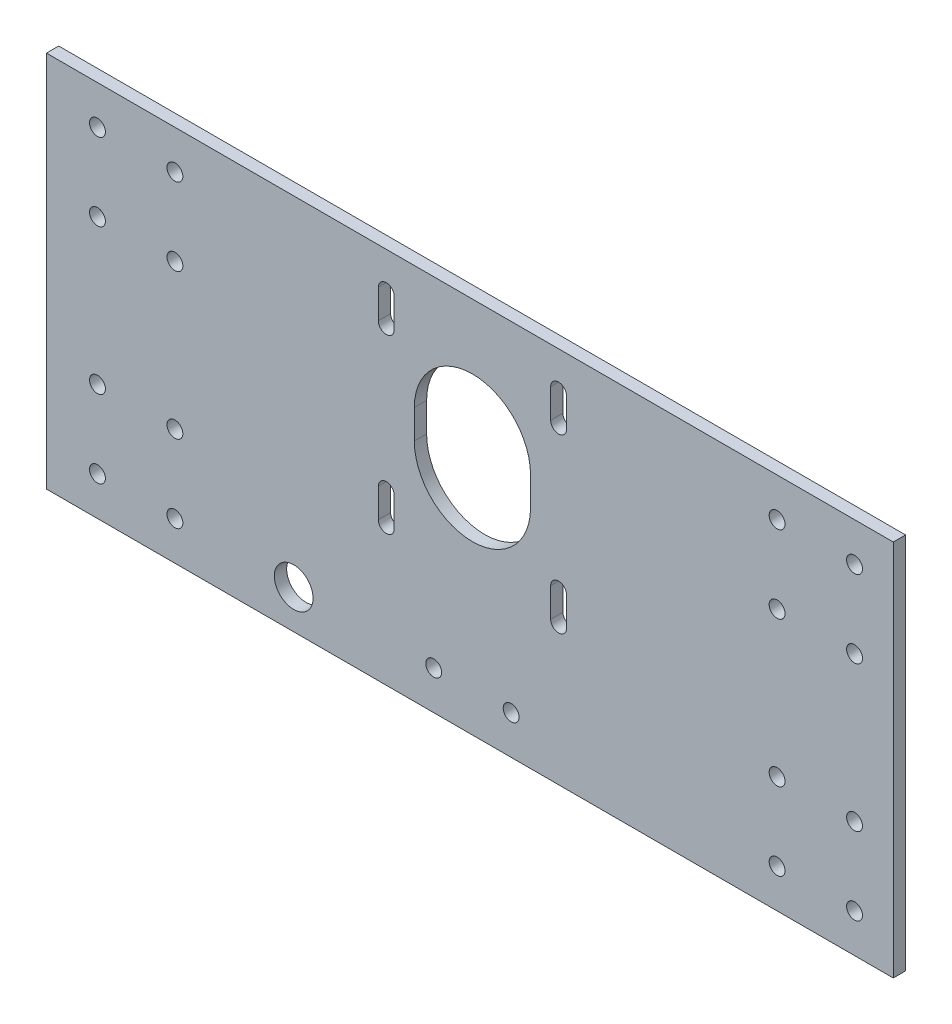
SolidWorks part; units mm, degrees
material "AISI Type A2 Tool Steel"
ref_plane "Front Plane" through (0, 0, 0) normal (0, 0, 1) x (1, 0, 0)
ref_plane "Top Plane" through (0, 0, 0) normal (0, 1, 0) x (1, 0, 0)
ref_plane "Right Plane" through (0, 0, 0) normal (1, 0, 0) x (0, 0, -1)
sketch "Sketch1" plane through (0, 0, 0) normal (0, 0, 1) x (1, 0, 0)
  line L0 (-44.5, -44.5) -> (-44.5, -29.5) construction
  line L1 (-44.5, 44.5) -> (44.5, 44.5) construction
  line L2 (-44.5, 44.5) -> (-44.5, -44.5) construction
  line L3 (-44.5, -44.5) -> (44.5, -44.5) construction
  line L4 (44.5, 44.5) -> (44.5, -44.5) construction
  line L5 (-44.5, 44.5) -> (44.5, -44.5) construction
  line L6 (-44.5, -44.5) -> (44.5, 44.5) construction
  line L7 (-48.6, -44.5) -> (-48.6, -29.5)
  line L8 (-40.4, -44.5) -> (-40.4, -29.5)
  line L9 (-44.5, 44.5) -> (-44.5, 59.5) construction
  line L10 (-48.6, 44.5) -> (-48.6, 59.5)
  line L11 (-40.4, 44.5) -> (-40.4, 59.5)
  line L12 (44.5, 44.5) -> (44.5, 59.5) construction
  line L13 (40.4, 44.5) -> (40.4, 59.5)
  line L14 (48.6, 44.5) -> (48.6, 59.5)
  line L15 (44.5, -44.5) -> (44.5, -29.5) construction
  line L16 (40.4, -44.5) -> (40.4, -29.5)
  line L17 (48.6, -44.5) -> (48.6, -29.5)
  line L18 (0, 0) -> (0, 15) construction
  line L19 (-30, 0) -> (-30, 15)
  line L20 (30, 0) -> (30, 15)
  line L21 (-220, -116.5) -> (217.35, -116.5)
  line L22 (217.35, -116.5) -> (217.35, 78.5)
  line L23 (217.35, 78.5) -> (-220, 78.5)
  line L24 (-220, 78.5) -> (-220, -116.5)
  line L25 (-173.65, 38.5) -> (-173.65, -76.5) construction
  line L26 (-193.65, -56.5) -> (-153.65, -56.5) construction
  line L27 (-193.65, -56.5) -> (-193.65, -96.5) construction
  line L28 (-193.65, -96.5) -> (-153.65, -96.5) construction
  line L29 (-153.65, -56.5) -> (-153.65, -96.5) construction
  line L30 (-193.65, -56.5) -> (-153.65, -96.5) construction
  line L31 (-193.65, -96.5) -> (-153.65, -56.5) construction
  line L32 (-193.65, 18.5) -> (-153.65, 18.5) construction
  line L33 (-193.65, 18.5) -> (-193.65, 58.5) construction
  line L34 (-193.65, 58.5) -> (-153.65, 58.5) construction
  line L35 (-153.65, 18.5) -> (-153.65, 58.5) construction
  line L36 (-193.65, 18.5) -> (-153.65, 58.5) construction
  line L37 (-193.65, 58.5) -> (-153.65, 18.5) construction
  line L38 (197.35, -96.5) -> (157.35, -96.5) construction
  line L39 (197.35, -96.5) -> (197.35, -56.5) construction
  line L40 (197.35, -56.5) -> (157.35, -56.5) construction
  line L41 (157.35, -96.5) -> (157.35, -56.5) construction
  line L42 (197.35, -96.5) -> (157.35, -56.5) construction
  line L43 (197.35, -56.5) -> (157.35, -96.5) construction
  line L44 (197.35, 18.5) -> (157.35, 18.5) construction
  line L45 (197.35, 18.5) -> (197.35, 58.5) construction
  line L46 (197.35, 58.5) -> (157.35, 58.5) construction
  line L47 (157.35, 18.5) -> (157.35, 58.5) construction
  line L48 (197.35, 18.5) -> (157.35, 58.5) construction
  line L49 (197.35, 58.5) -> (157.35, 18.5) construction
  line L50 (-20, -96.5) -> (20, -96.5) construction
  line L51 (177.35, 38.5) -> (177.35, -76.5) construction
  line L52 (-213.65, -42.4115) -> (-133.65, -42.4115) construction
  line L53 (-213.65, -42.4115) -> (-213.65, -110.5885) construction
  line L54 (-213.65, -110.5885) -> (-133.65, -110.5885) construction
  line L55 (-133.65, -42.4115) -> (-133.65, -110.5885) construction
  line L56 (-213.65, -42.4115) -> (-133.65, -110.5885) construction
  line L57 (-213.65, -110.5885) -> (-133.65, -42.4115) construction
  line L58 (0, -96.5) -> (0, -116.5) construction
  line L60 (-127.3, -33.789) -> (-133.65, -33.789) construction
  line L61 (-127.3, -33.789) -> (-127.3, -116.5) construction
  line L62 (-127.3, -116.5) -> (-133.65, -116.5) construction
  line L63 (-133.65, -33.789) -> (-133.65, -116.5) construction
  line L64 (-127.3, -33.789) -> (-133.65, -116.5) construction
  line L65 (-127.3, -116.5) -> (-133.65, -33.789) construction
  line L66 (-127.3, -76.5) -> (-57.3, -76.5) construction
  line L67 (-127.3, -76.5) -> (-127.3, -116.5) construction
  line L68 (-127.3, -116.5) -> (-57.3, -116.5) construction
  line L69 (-57.3, -76.5) -> (-57.3, -116.5) construction
  line L70 (-127.3, -76.5) -> (-57.3, -116.5) construction
  line L71 (-127.3, -116.5) -> (-57.3, -76.5) construction
  arc A0 (-48.6, -44.5) -> (-40.4, -44.5) centre (-44.5, -44.5) ccw
  arc A1 (-40.4, -29.5) -> (-48.6, -29.5) centre (-44.5, -29.5) ccw
  arc A2 (-48.6, 44.5) -> (-40.4, 44.5) centre (-44.5, 44.5) ccw
  arc A3 (-40.4, 59.5) -> (-48.6, 59.5) centre (-44.5, 59.5) ccw
  arc A4 (40.4, 44.5) -> (48.6, 44.5) centre (44.5, 44.5) ccw
  arc A5 (48.6, 59.5) -> (40.4, 59.5) centre (44.5, 59.5) ccw
  arc A6 (40.4, -44.5) -> (48.6, -44.5) centre (44.5, -44.5) ccw
  arc A7 (48.6, -29.5) -> (40.4, -29.5) centre (44.5, -29.5) ccw
  arc A8 (-30, 0) -> (30, 0) centre (0, 0) ccw
  arc A9 (30, 15) -> (-30, 15) centre (0, 15) ccw
  circle A10 centre (-193.65, 58.5) radius 4.1
  circle A11 centre (-153.65, 58.5) radius 4.1
  circle A12 centre (-153.65, 18.5) radius 4.1
  circle A13 centre (-193.65, 18.5) radius 4.1
  circle A14 centre (-193.65, -56.5) radius 4.1
  circle A15 centre (-153.65, -56.5) radius 4.1
  circle A16 centre (-153.65, -96.5) radius 4.1
  circle A17 centre (-193.65, -96.5) radius 4.1
  circle A18 centre (157.35, -56.5) radius 4.1
  circle A19 centre (197.35, -56.5) radius 4.1
  circle A20 centre (197.35, -96.5) radius 4.1
  circle A21 centre (157.35, -96.5) radius 4.1
  circle A22 centre (157.35, 18.5) radius 4.1
  circle A23 centre (197.35, 18.5) radius 4.1
  circle A24 centre (197.35, 58.5) radius 4.1
  circle A25 centre (157.35, 58.5) radius 4.1
  circle A26 centre (-92.3, -96.5) radius 10
  circle A27 centre (-20, -96.5) radius 4.1
  circle A28 centre (20, -96.5) radius 4.1
  point P0 (0, 0)
  point P6 (-44.5, -37)
  point P12 (-44.5, 52)
  point P18 (44.5, 52)
  point P24 (44.5, -37)
  point P30 (0, 7.5)
  point P39 (-173.65, -76.5)
  point P46 (-173.65, 38.5)
  point P51 (177.35, -76.5)
  point P56 (177.35, 38.5)
  point P82 (-173.65, -96.5)
  point P94 (-130.475, -75.1445)
  dimension "D10" = 8.2
  dimension "D20" = 20
  dimension "D24" = 8.2
  dimension "D1" = 89
  dimension "D2" = 8.2
  dimension "D3" = 15
  dimension "D4" = 15
  dimension "D5" = 60
  dimension "D6" = 220
  dimension "D7" = 437.35
  dimension "D8" = 72
  dimension "D9" = 195
  dimension "D11" = 40
  dimension "D12" = 26.35
  dimension "D13" = 20
  dimension "D14" = 20
  dimension "D15" = 20
  dimension "D16" = 20
  dimension "D17" = 20
  dimension "D18" = 80
  dimension "D19" = 6.35
  dimension "D21" = 20
  dimension "D22" = 20
  dimension "D23" = 40
  dimension "D25" = 41.35
  dimension "D26" = 70
extrude "Boss-Extrude1" add sketch "Sketch1" along normal blind 6.35
